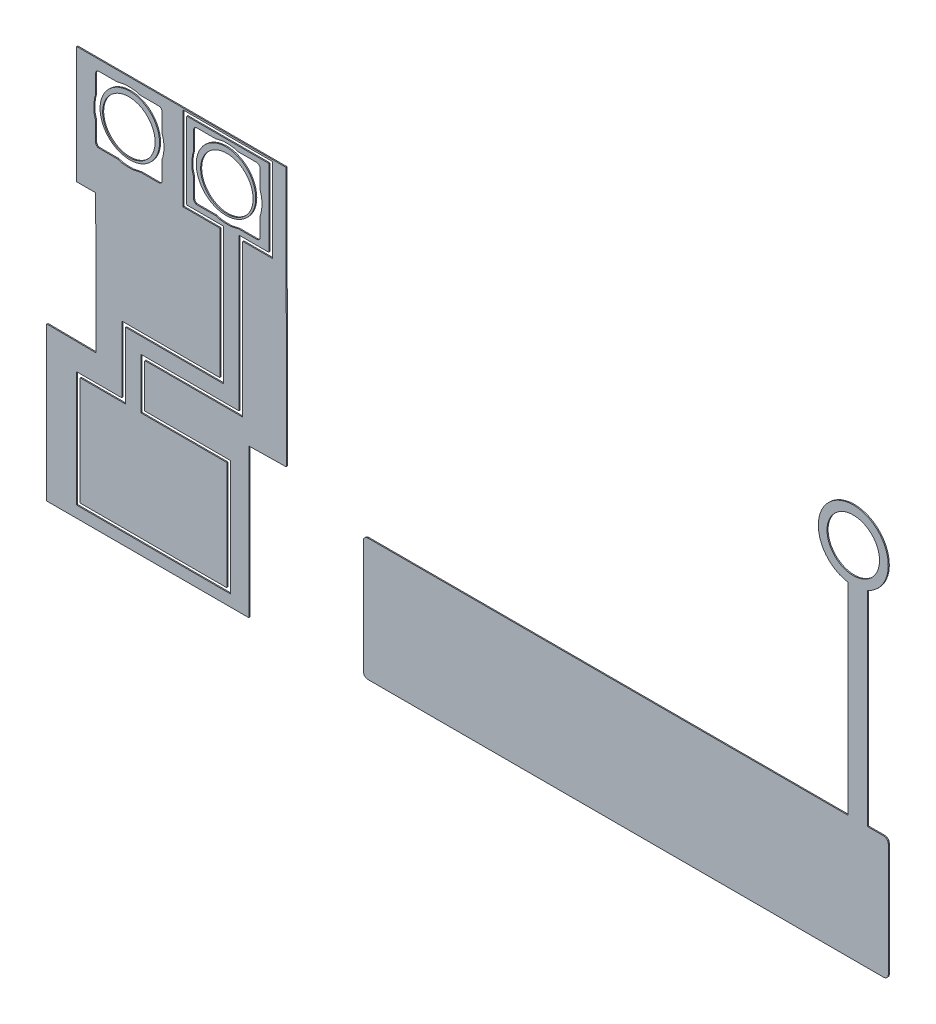
SolidWorks part; units mm, degrees
material "Pure Gold"
ref_plane "Front Plane" through (0, 0, 0) normal (0, 0, 1) x (1, 0, 0)
ref_plane "Top Plane" through (0, 0, 0) normal (0, 1, 0) x (1, 0, 0)
ref_plane "Right Plane" through (0, 0, 0) normal (1, 0, 0) x (0, 0, -1)
sketch "Sketch1" plane through (0, 0, 0) normal (0, 0, 1) x (1, 0, 0)
  line L1 (23.5642, 12.1088) -> (23.5642, 9.7088)
  line L6 (24.7062, 9.7088) -> (23.5642, 9.7088)
  line L7 (25.2562, 9.7088) -> (26.1562, 9.7088)
  line L8 (26.1562, 9.7088) -> (26.1562, 12.1088)
  line L9 (26.1562, 12.1088) -> (23.5642, 12.1088)
  line L344 (24.7062, 9.7088) -> (24.7062, 4.2038)
  line L346 (25.2562, 4.2038) -> (25.2562, 9.7088)
  line L348 (5.8202, 12.0588) -> (5.8102, 12.0548)
  line L349 (8.1422, 12.0588) -> (5.8202, 12.0588)
  line L350 (8.1522, 12.0548) -> (8.1422, 12.0588)
  line L351 (8.1562, 12.0448) -> (8.1522, 12.0548)
  line L352 (8.1562, 10.9078) -> (8.1562, 12.0448)
  line L354 (7.9552, 11.0098) -> (7.9602, 10.9078)
  line L355 (7.9502, 11.1108) -> (7.9552, 11.0098)
  line L356 (7.9072, 11.2778) -> (7.9502, 11.1108)
  line L357 (7.9062, 11.2808) -> (7.9072, 11.2778)
  line L358 (7.9062, 11.8188) -> (7.9062, 11.2808)
  line L359 (7.9012, 11.8478) -> (7.9062, 11.8188)
  line L360 (7.8782, 11.8808) -> (7.9012, 11.8478)
  line L361 (7.8452, 11.9038) -> (7.8782, 11.8808)
  line L362 (7.8162, 11.9098) -> (7.8452, 11.9038)
  line L363 (7.2712, 11.9098) -> (7.8162, 11.9098)
  line L364 (7.2672, 11.9098) -> (7.2712, 11.9098)
  line L365 (7.1582, 11.9438) -> (7.2672, 11.9098)
  line L366 (7.0072, 11.9598) -> (7.1582, 11.9438)
  line L367 (6.8542, 11.9598) -> (7.0072, 11.9598)
  line L368 (6.6552, 11.9188) -> (6.8542, 11.9598)
  line L369 (6.6372, 11.9108) -> (6.6552, 11.9188)
  line L370 (6.6312, 11.9098) -> (6.6372, 11.9108)
  line L371 (6.0962, 11.9098) -> (6.6312, 11.9098)
  line L372 (6.0672, 11.9038) -> (6.0962, 11.9098)
  line L373 (6.0332, 11.8808) -> (6.0672, 11.9038)
  line L374 (6.0112, 11.8478) -> (6.0332, 11.8808)
  line L375 (6.0062, 11.8188) -> (6.0112, 11.8478)
  line L376 (6.0062, 11.2758) -> (6.0062, 11.8188)
  line L377 (6.0052, 11.2708) -> (6.0062, 11.2758)
  line L378 (5.9822, 11.2108) -> (6.0052, 11.2708)
  line L379 (5.9522, 11.0098) -> (5.9822, 11.2108)
  line L380 (5.9622, 10.8068) -> (5.9522, 11.0098)
  line L381 (5.9882, 10.7068) -> (5.9622, 10.8068)
  line L382 (6.0052, 10.6398) -> (5.9882, 10.7068)
  line L383 (6.0062, 10.6368) -> (6.0052, 10.6398)
  line L384 (6.0062, 10.0988) -> (6.0062, 10.6368)
  line L385 (6.0112, 10.0698) -> (6.0062, 10.0988)
  line L386 (6.0332, 10.0358) -> (6.0112, 10.0698)
  line L387 (6.0672, 10.0138) -> (6.0332, 10.0358)
  line L388 (6.0962, 10.0088) -> (6.0672, 10.0138)
  line L389 (6.6412, 10.0088) -> (6.0962, 10.0088)
  line L390 (6.6452, 10.0078) -> (6.6412, 10.0088)
  line L391 (6.7542, 9.9738) -> (6.6452, 10.0078)
  line L392 (6.9052, 9.9588) -> (6.7542, 9.9738)
  line L393 (7.0582, 9.9588) -> (6.9052, 9.9588)
  line L394 (7.2572, 9.9998) -> (7.0582, 9.9588)
  line L395 (7.2632, 10.0018) -> (7.2572, 9.9998)
  line L396 (7.2752, 10.0068) -> (7.2632, 10.0018)
  line L397 (7.2812, 10.0088) -> (7.2752, 10.0068)
  line L398 (7.8162, 10.0088) -> (7.2812, 10.0088)
  line L399 (7.8452, 10.0138) -> (7.8162, 10.0088)
  line L400 (7.8782, 10.0358) -> (7.8452, 10.0138)
  line L401 (7.9012, 10.0698) -> (7.8782, 10.0358)
  line L402 (7.9062, 10.0988) -> (7.9012, 10.0698)
  line L403 (7.9062, 10.6418) -> (7.9062, 10.0988)
  line L404 (7.9072, 10.6468) -> (7.9062, 10.6418)
  line L405 (7.9302, 10.7068) -> (7.9072, 10.6468)
  line L406 (7.9452, 10.8068) -> (7.9302, 10.7068)
  line L407 (7.9602, 10.9078) -> (7.9452, 10.8068)
  line L409 (8.1562, 9.8728) -> (8.1562, 10.9078)
  line L410 (8.1522, 9.8628) -> (8.1562, 9.8728)
  line L411 (8.1422, 9.8588) -> (8.1522, 9.8628)
  line L412 (7.4062, 9.8588) -> (8.1422, 9.8588)
  line L413 (7.3062, 9.8588) -> (7.4062, 9.8588)
  line L414 (7.3062, 5.5228) -> (7.3062, 9.8588)
  line L415 (7.3022, 5.5128) -> (7.3062, 5.5228)
  line L416 (7.2922, 5.5088) -> (7.3022, 5.5128)
  line L417 (4.5062, 5.5088) -> (7.2922, 5.5088)
  line L418 (4.5062, 4.0588) -> (4.5062, 5.5088)
  line L419 (6.9422, 4.0588) -> (4.5062, 4.0588)
  line L420 (6.9522, 4.0548) -> (6.9422, 4.0588)
  line L421 (6.9562, 4.0448) -> (6.9522, 4.0548)
  line L422 (6.9562, 0.9728) -> (6.9562, 4.0448)
  line L423 (6.9522, 0.9628) -> (6.9562, 0.9728)
  line L424 (6.9422, 0.9588) -> (6.9522, 0.9628)
  line L425 (2.7702, 0.9588) -> (6.9422, 0.9588)
  line L426 (2.7602, 0.9628) -> (2.7702, 0.9588)
  line L427 (2.7562, 0.9728) -> (2.7602, 0.9628)
  line L428 (2.7562, 4.0448) -> (2.7562, 0.9728)
  line L429 (2.7602, 4.0548) -> (2.7562, 4.0448)
  line L430 (2.7702, 4.0588) -> (2.7602, 4.0548)
  line L431 (3.9562, 4.0588) -> (2.7702, 4.0588)
  line L432 (4.0562, 4.0588) -> (3.9562, 4.0588)
  line L433 (4.0562, 5.9448) -> (4.0562, 4.0588)
  line L434 (4.0602, 5.9548) -> (4.0562, 5.9448)
  line L435 (4.0702, 5.9588) -> (4.0602, 5.9548)
  line L436 (6.8562, 5.9588) -> (4.0702, 5.9588)
  line L437 (6.8562, 6.0588) -> (6.8562, 5.9588)
  line L438 (6.8562, 9.7588) -> (6.8562, 6.0588)
  line L439 (6.8562, 9.8588) -> (6.8562, 9.7588)
  line L440 (5.8202, 9.8588) -> (6.8562, 9.8588)
  line L441 (5.8102, 9.8628) -> (5.8202, 9.8588)
  line L442 (5.8062, 9.8728) -> (5.8102, 9.8628)
  line L443 (5.8062, 12.0448) -> (5.8062, 9.8728)
  line L444 (5.8102, 12.0548) -> (5.8062, 12.0448)
  line L445 (2.6742, 12.2088) -> (2.6642, 12.2048)
  line L446 (8.6292, 12.2088) -> (2.6742, 12.2088)
  line L447 (8.6392, 12.2048) -> (8.6292, 12.2088)
  line L448 (8.6432, 12.1948) -> (8.6392, 12.2048)
  line L449 (8.6442, 12.1588) -> (8.6432, 12.1948)
  line L451 (5.8062, 12.1588) -> (8.2562, 12.1588)
  line L452 (5.7062, 12.1588) -> (5.8062, 12.1588)
  line L453 (5.7062, 10.9078) -> (5.7062, 12.1588)
  line L455 (5.1552, 11.0098) -> (5.1602, 10.9078)
  line L456 (5.1502, 11.1108) -> (5.1552, 11.0098)
  line L457 (5.1072, 11.2778) -> (5.1502, 11.1108)
  line L458 (5.1072, 11.2808) -> (5.1072, 11.2778)
  line L459 (5.1072, 11.8188) -> (5.1072, 11.2808)
  line L460 (5.1012, 11.8478) -> (5.1072, 11.8188)
  line L461 (5.0792, 11.8808) -> (5.1012, 11.8478)
  line L462 (5.0452, 11.9038) -> (5.0792, 11.8808)
  line L463 (5.0162, 11.9098) -> (5.0452, 11.9038)
  line L464 (4.4712, 11.9098) -> (5.0162, 11.9098)
  line L465 (4.4672, 11.9098) -> (4.4712, 11.9098)
  line L466 (4.3582, 11.9438) -> (4.4672, 11.9098)
  line L467 (4.2072, 11.9598) -> (4.3582, 11.9438)
  line L468 (4.0542, 11.9598) -> (4.2072, 11.9598)
  line L469 (3.8552, 11.9188) -> (4.0542, 11.9598)
  line L470 (3.8362, 11.9108) -> (3.8552, 11.9188)
  line L471 (3.8312, 11.9098) -> (3.8362, 11.9108)
  line L472 (3.2962, 11.9098) -> (3.8312, 11.9098)
  line L473 (3.2672, 11.9038) -> (3.2962, 11.9098)
  line L474 (3.2332, 11.8808) -> (3.2672, 11.9038)
  line L475 (3.2112, 11.8478) -> (3.2332, 11.8808)
  line L476 (3.2052, 11.8188) -> (3.2112, 11.8478)
  line L477 (3.2052, 11.2758) -> (3.2052, 11.8188)
  line L478 (3.2052, 11.2708) -> (3.2052, 11.2758)
  line L479 (3.1822, 11.2108) -> (3.2052, 11.2708)
  line L480 (3.1522, 11.0098) -> (3.1822, 11.2108)
  line L481 (3.1622, 10.8068) -> (3.1522, 11.0098)
  line L482 (3.1882, 10.7068) -> (3.1622, 10.8068)
  line L483 (3.2052, 10.6398) -> (3.1882, 10.7068)
  line L484 (3.2052, 10.6368) -> (3.2052, 10.6398)
  line L485 (3.2052, 10.0988) -> (3.2052, 10.6368)
  line L486 (3.2112, 10.0698) -> (3.2052, 10.0988)
  line L487 (3.2332, 10.0358) -> (3.2112, 10.0698)
  line L488 (3.2672, 10.0138) -> (3.2332, 10.0358)
  line L489 (3.2962, 10.0088) -> (3.2672, 10.0138)
  line L490 (3.8412, 10.0088) -> (3.2962, 10.0088)
  line L491 (3.8452, 10.0078) -> (3.8412, 10.0088)
  line L492 (3.9542, 9.9738) -> (3.8452, 10.0078)
  line L493 (4.1052, 9.9588) -> (3.9542, 9.9738)
  line L494 (4.2582, 9.9588) -> (4.1052, 9.9588)
  line L495 (4.4572, 9.9998) -> (4.2582, 9.9588)
  line L496 (4.4632, 10.0018) -> (4.4572, 9.9998)
  line L497 (4.4762, 10.0068) -> (4.4632, 10.0018)
  line L498 (4.4812, 10.0088) -> (4.4762, 10.0068)
  line L499 (5.0162, 10.0088) -> (4.4812, 10.0088)
  line L500 (5.0452, 10.0138) -> (5.0162, 10.0088)
  line L501 (5.0792, 10.0358) -> (5.0452, 10.0138)
  line L502 (5.1012, 10.0698) -> (5.0792, 10.0358)
  line L503 (5.1072, 10.0988) -> (5.1012, 10.0698)
  line L504 (5.1072, 10.6418) -> (5.1072, 10.0988)
  line L505 (5.1072, 10.6468) -> (5.1072, 10.6418)
  line L506 (5.1302, 10.7068) -> (5.1072, 10.6468)
  line L507 (5.1452, 10.8068) -> (5.1302, 10.7068)
  line L508 (5.1602, 10.9078) -> (5.1452, 10.8068)
  line L510 (5.7062, 9.7588) -> (5.7062, 10.9078)
  line L511 (6.7422, 9.7588) -> (5.7062, 9.7588)
  line L512 (6.7522, 9.7548) -> (6.7422, 9.7588)
  line L513 (6.7562, 9.7448) -> (6.7522, 9.7548)
  line L514 (6.7562, 6.0728) -> (6.7562, 9.7448)
  line L515 (6.7522, 6.0628) -> (6.7562, 6.0728)
  line L516 (6.7422, 6.0588) -> (6.7522, 6.0628)
  line L517 (4.0562, 6.0588) -> (6.7422, 6.0588)
  line L518 (3.9562, 6.0588) -> (4.0562, 6.0588)
  line L519 (3.9562, 4.1728) -> (3.9562, 6.0588)
  line L520 (3.9522, 4.1628) -> (3.9562, 4.1728)
  line L521 (3.9422, 4.1588) -> (3.9522, 4.1628)
  line L522 (2.6562, 4.1588) -> (3.9422, 4.1588)
  line L523 (2.6562, 0.8588) -> (2.6562, 4.1588)
  line L524 (7.0562, 0.8588) -> (2.6562, 0.8588)
  line L525 (7.0562, 4.0588) -> (7.0562, 0.8588)
  line L526 (7.0562, 4.1588) -> (7.0562, 4.0588)
  line L527 (5.3562, 4.1588) -> (7.0562, 4.1588)
  line L528 (4.6202, 4.1588) -> (5.3562, 4.1588)
  line L529 (4.6102, 4.1628) -> (4.6202, 4.1588)
  line L530 (4.6062, 4.1728) -> (4.6102, 4.1628)
  line L531 (4.6062, 5.3948) -> (4.6062, 4.1728)
  line L532 (4.6102, 5.4048) -> (4.6062, 5.3948)
  line L533 (4.6202, 5.4088) -> (4.6102, 5.4048)
  line L534 (7.4062, 5.4088) -> (4.6202, 5.4088)
  line L535 (7.4062, 5.5088) -> (7.4062, 5.4088)
  line L536 (7.4062, 6.1588) -> (7.4062, 5.5088)
  line L537 (7.4062, 9.7448) -> (7.4062, 6.1588)
  line L538 (7.4102, 9.7548) -> (7.4062, 9.7448)
  line L539 (7.4202, 9.7588) -> (7.4102, 9.7548)
  line L540 (8.2562, 9.7588) -> (7.4202, 9.7588)
  line L541 (8.2562, 9.8588) -> (8.2562, 9.7588)
  line L542 (8.2562, 11.9088) -> (8.2562, 9.8588)
  line L543 (8.2562, 12.0588) -> (8.2562, 11.9088)
  line L544 (8.2562, 12.1588) -> (8.2562, 12.0588)
  line L546 (8.6562, 7.1888) -> (8.6442, 12.1588)
  line L547 (8.6562, 4.8128) -> (8.6562, 7.1888)
  line L548 (8.6522, 4.8028) -> (8.6562, 4.8128)
  line L549 (8.6422, 4.7988) -> (8.6522, 4.8028)
  line L550 (7.5922, 4.7818) -> (8.6422, 4.7988)
  line L551 (7.5922, 0.5458) -> (7.5922, 4.7818)
  line L552 (7.5882, 0.5358) -> (7.5922, 0.5458)
  line L553 (7.5782, 0.5318) -> (7.5882, 0.5358)
  line L554 (1.8202, 0.5318) -> (7.5782, 0.5318)
  line L555 (1.8102, 0.5358) -> (1.8202, 0.5318)
  line L556 (1.8062, 0.5458) -> (1.8102, 0.5358)
  line L557 (1.8062, 4.9018) -> (1.8062, 0.5458)
  line L558 (1.8102, 4.9118) -> (1.8062, 4.9018)
  line L559 (1.8202, 4.9158) -> (1.8102, 4.9118)
  line L560 (3.2182, 4.9028) -> (1.8202, 4.9158)
  line L561 (3.2072, 8.8598) -> (3.2182, 4.9028)
  line L562 (2.6702, 8.8588) -> (3.2072, 8.8598)
  line L563 (2.6602, 8.8628) -> (2.6702, 8.8588)
  line L564 (2.6562, 8.8728) -> (2.6602, 8.8628)
  line L565 (2.6602, 12.1948) -> (2.6562, 8.8728)
  line L566 (2.6642, 12.2048) -> (2.6602, 12.1948)
  line L637 (25.7322, 4.2038) -> (25.2562, 4.2038)
  line L638 (25.7832, 4.1928) -> (25.7322, 4.2038)
  line L639 (25.8362, 4.1468) -> (25.7832, 4.1928)
  line L640 (25.8562, 4.0798) -> (25.8362, 4.1468)
  line L641 (25.8562, 0.8278) -> (25.8562, 4.0798)
  line L642 (25.8452, 0.7768) -> (25.8562, 0.8278)
  line L643 (25.7992, 0.7238) -> (25.8452, 0.7768)
  line L644 (25.7322, 0.7038) -> (25.7992, 0.7238)
  line L645 (10.9802, 0.7038) -> (25.7322, 0.7038)
  line L646 (10.9292, 0.7148) -> (10.9802, 0.7038)
  line L647 (10.8762, 0.7608) -> (10.9292, 0.7148)
  line L648 (10.8562, 0.8278) -> (10.8762, 0.7608)
  line L649 (10.8562, 4.0798) -> (10.8562, 0.8278)
  line L650 (10.8672, 4.1318) -> (10.8562, 4.0798)
  line L651 (10.9132, 4.1848) -> (10.8672, 4.1318)
  line L652 (10.9802, 4.2038) -> (10.9132, 4.1848)
  line L653 (24.7062, 4.2038) -> (10.9802, 4.2038)
  line L656 (3.3062, 10.1088) -> (5.0062, 10.1088)
  line L657 (3.3062, 11.8088) -> (3.3062, 10.1088)
  line L658 (5.0062, 11.8088) -> (3.3062, 11.8088)
  line L659 (5.0062, 10.1088) -> (5.0062, 11.8088)
  line L660 (6.1062, 10.1088) -> (7.8062, 10.1088)
  line L661 (6.1062, 11.8088) -> (6.1062, 10.1088)
  line L662 (7.8062, 11.8088) -> (6.1062, 11.8088)
  line L663 (7.8062, 10.1088) -> (7.8062, 11.8088)
extrude "Boss-Extrude1" add sketch "Sketch1" along normal blind 0.03
sketch "Sketch2" plane through (0, 0, 0.03) normal (0, 0, 1) x (1, 0, 0)
  line L0 (4.2582, 9.9588) -> (4.1052, 9.9588) construction
  line L1 (6.8542, 11.9598) -> (7.0072, 11.9598) construction
  circle A0 centre (4.1817, 11.0098) radius 0.85
  circle A1 centre (6.9307, 11.0098) radius 0.85
  point P6 (4.1817, 9.9588)
  point P10 (6.9307, 11.9598)
  dimension "D1" = 0
  dimension "D2" = 0
  dimension "D3" = 1.7
  dimension "D4" = 0
  dimension "D5" = 0
  dimension "D6" = 1.7
extrude "Boss-Extrude2" add sketch "Sketch2" against normal blind 0.03 separate body
fillet "Fillet1" radius 1 4 edges at (23.5642, 9.7088, 0.015) (26.1562, 9.7088, 0.015) (23.5642, 12.1088, 0.015) (26.1562, 12.1088, 0.015)
sketch "Sketch3" plane through (0, 0, 0) normal (0, 0, -1) x (-1, 0, 0)
  circle A0 centre (-24.8557, 10.9593) radius 0.75
  circle A1 centre (-6.9557, 10.9593) radius 0.75
  circle A2 centre (-4.1557, 10.9593) radius 0.75
extrude "Cut-Extrude1" cut sketch "Sketch3" against normal through all both
sketch "Sketch4" plane through (0, 0, 0.03) normal (0, 0, 1) x (1, 0, 0)
  line L0 (24.7062, 9.7088) -> (24.7062, 9.9705)
  line L1 (25.2562, 9.7088) -> (25.2562, 10.043)
  line L2 (25.2562, 9.7088) -> (25.7442, 9.1246)
  line L3 (25.7442, 9.1246) -> (27.2505, 10.1451)
  line L4 (27.2505, 10.1451) -> (27.0548, 12.6299)
  line L5 (27.0548, 12.6299) -> (23.2676, 12.6299)
  line L6 (23.2676, 12.6299) -> (22.6039, 9.8904)
  line L7 (22.6039, 9.8904) -> (23.6125, 8.8883)
  line L8 (23.6125, 8.8883) -> (24.7062, 9.7088)
  arc A0 (25.2562, 10.043) -> (24.7062, 9.9705) centre (24.8557, 10.9593) ccw
  dimension "D1" = 2
extrude "Cut-Extrude2" cut sketch "Sketch4" against normal through all both
